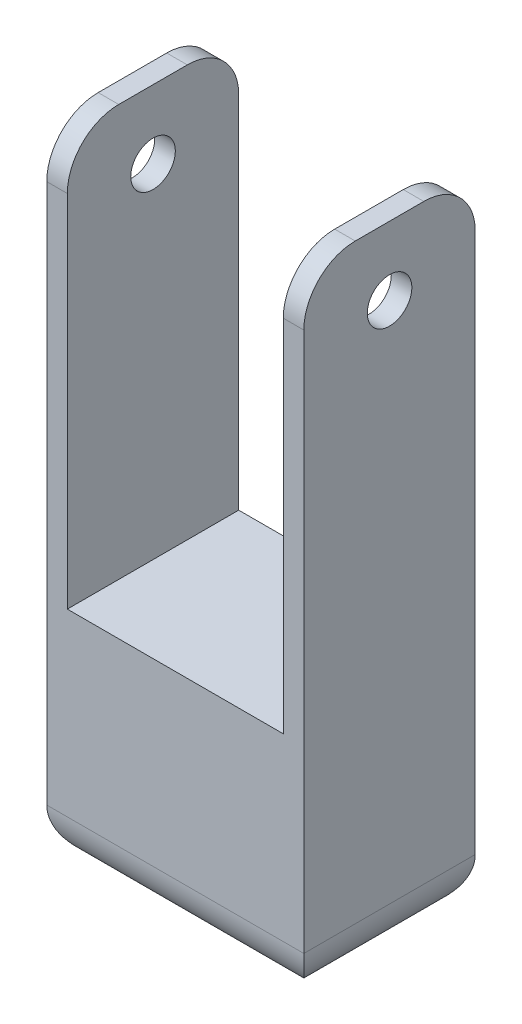
SolidWorks part; units mm, degrees
ref_plane "Front Plane" through (0, 0, 0) normal (0, 0, 1) x (1, 0, 0)
ref_plane "Top Plane" through (0, 0, 0) normal (0, 1, 0) x (1, 0, 0)
ref_plane "Right Plane" through (0, 0, 0) normal (1, 0, 0) x (0, 0, -1)
sketch "Sketch1" plane through (0, 0, 0) normal (0, 1, 0) x (1, 0, 0)
  line L1 (-19.05, 12.7) -> (19.05, 12.7)
  line L2 (-19.05, 12.7) -> (-19.05, -12.7)
  line L3 (-19.05, -12.7) -> (19.05, -12.7)
  line L4 (19.05, 12.7) -> (19.05, -12.7)
  line L5 (-19.05, 12.7) -> (19.05, -12.7) construction
  line L6 (-19.05, -12.7) -> (19.05, 12.7) construction
  point P0 (0, 0)
  dimension "D1" = 38.1
  dimension "D2" = 25.4
extrude "Boss-Extrude1" add sketch "Sketch1" along normal blind 63.5
sketch "Sketch2" plane through (0, 63.5, 0) normal (0, 1, 0) x (1, 0, 0)
  line L0 (19.05, 12.7) -> (-19.05, 12.7) construction
  line L1 (-16.002, 12.7) -> (16.002, 12.7)
  line L2 (-16.002, 12.7) -> (-16.002, -12.7)
  line L3 (-16.002, -12.7) -> (16.002, -12.7)
  line L4 (16.002, 12.7) -> (16.002, -12.7)
  line L5 (-19.05, -12.7) -> (19.05, -12.7) construction
  dimension "D1" = 32.004
  dimension "D2" = 16.002
extrude "Cut-Extrude1" cut sketch "Sketch2" against normal blind 60.96
sketch "Sketch3" plane through (-19.05, 0, 0) normal (-1, 0, 0) x (0, 0, 1)
  line L1 (-12.7, 63.5) -> (12.7, 63.5) construction
  circle A0 centre (0, 53.34) radius 3.302
  dimension "D1" = 6.604
  dimension "D2" = 10.16
extrude "Cut-Extrude2" cut sketch "Sketch3" against normal through all
fillet "Fillet1" radius 7.62 4 edges at (17.526, 63.5, 12.7) (17.526, 63.5, -12.7) (-17.526, 63.5, 12.7) (-17.526, 63.5, -12.7)
sketch "Sketch4" plane through (0, 0, 0) normal (0, -1, 0) x (1, 0, 0)
  line L1 (-19.05, 12.7) -> (19.05, 12.7)
  line L2 (-19.05, 12.7) -> (-19.05, -12.7)
  line L3 (-19.05, -12.7) -> (19.05, -12.7)
  line L4 (19.05, 12.7) -> (19.05, -12.7)
extrude "Boss-Extrude2" add sketch "Sketch4" along normal blind 31.75
fillet "Fillet2" radius 7.62 4 edges at (0, -31.75, 12.7) (19.05, -31.75, 0) (0, -31.75, -12.7) (-19.05, -31.75, 0)
